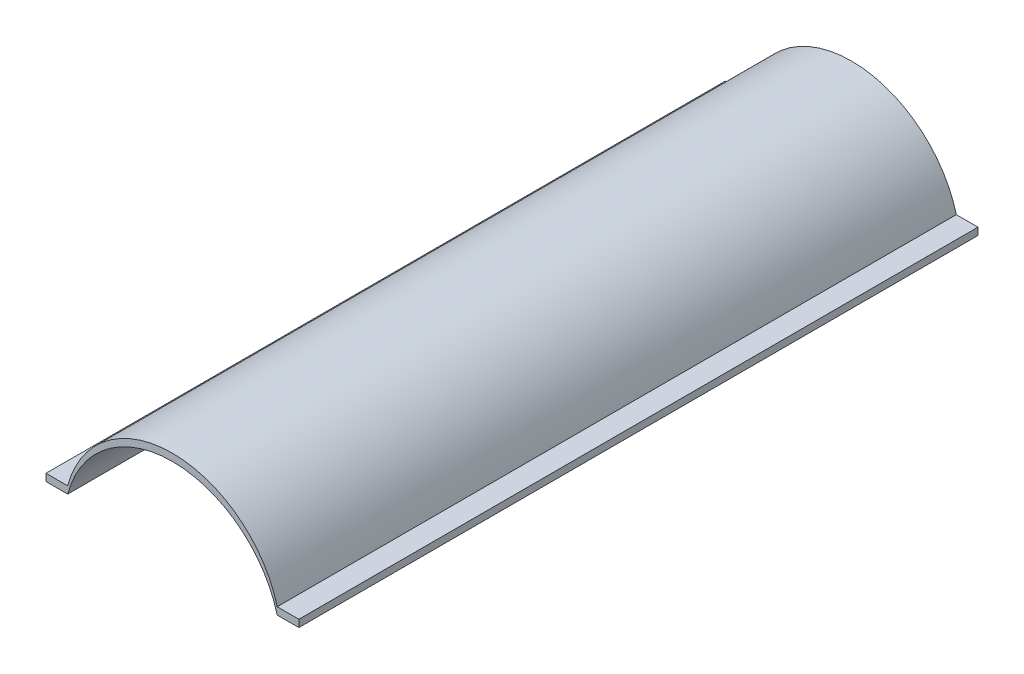
SolidWorks part; units mm, degrees
material "PETG"
ref_plane "Front Plane" through (0, 0, 0) normal (0, 0, 1) x (1, 0, 0)
ref_plane "Top Plane" through (0, 0, 0) normal (0, 1, 0) x (1, 0, 0)
ref_plane "Right Plane" through (0, 0, 0) normal (1, 0, 0) x (0, 0, -1)
sketch "Sketch1" plane through (0, 0, 0) normal (0, 0, 1) x (1, 0, 0)
  line L0 (-8.457, 0.5801) -> (-8.457, 2.5801)
  line L1 (-8.457, 2.5801) -> (-2.457, 2.5801)
  line L2 (-8.457, 0.5801) -> (-2.457, 0.5801)
  line L4 (55.543, 0.5801) -> (61.543, 0.5801)
  line L5 (61.543, 0.5801) -> (61.543, 2.5801)
  line L6 (61.543, 2.5801) -> (55.543, 2.5801)
  arc A7 (-2.457, 2.5801) -> (55.543, 2.5801) centre (26.543, -5.101) cw
  arc A8 (-2.457, 0.5801) -> (55.543, 0.5801) centre (26.543, -7.101) cw
  dimension "D4" = 6
  dimension "D8" = 30
  dimension "D9" = 30
  dimension "D1" = 6
  dimension "D2" = 2
  dimension "D3" = 58
  dimension "D5" = 6
  dimension "D6" = 6
  dimension "D7" = 2
extrude "Boss-Extrude1" add sketch "Sketch1" along normal blind 188
